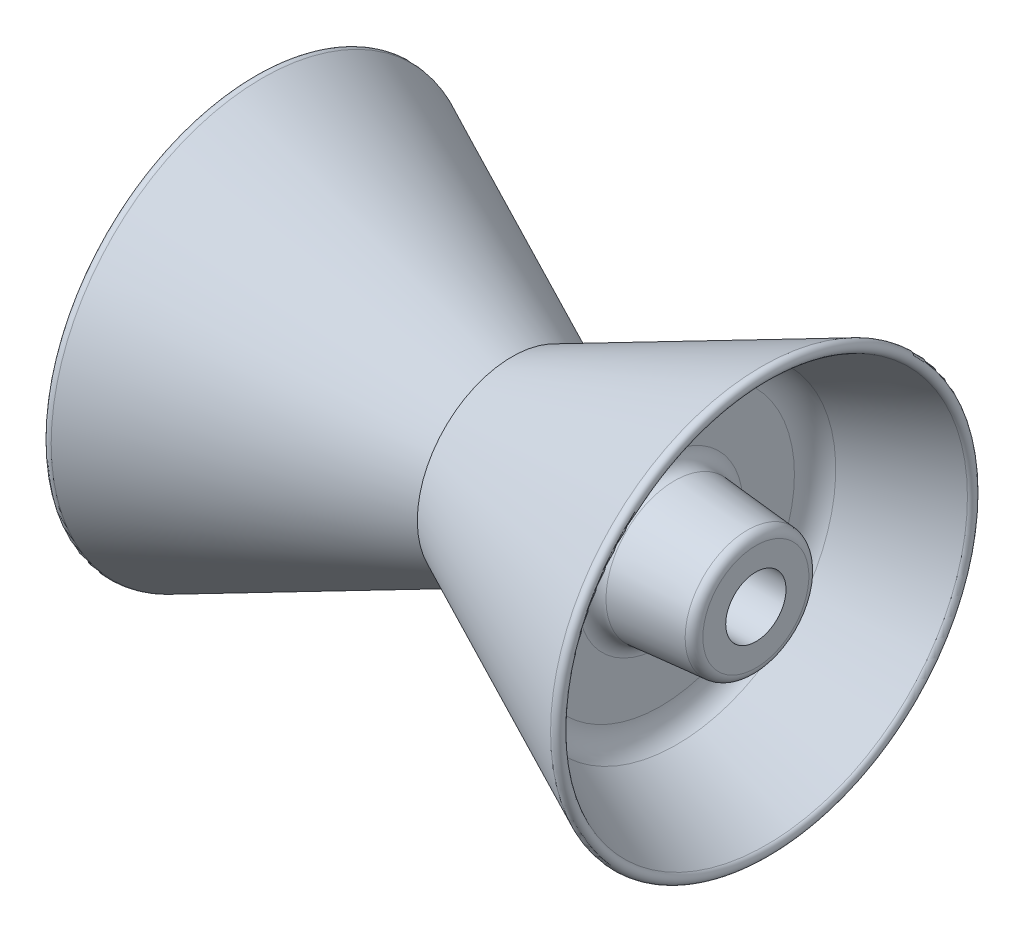
SolidWorks part; units mm, degrees
ref_plane "Front Plane" through (0, 0, 0) normal (0, 0, 1) x (1, 0, 0)
ref_plane "Top Plane" through (0, 0, 0) normal (0, 1, 0) x (1, 0, 0)
ref_plane "Right Plane" through (0, 0, 0) normal (1, 0, 0) x (0, 0, -1)
sketch "Sketch1" plane through (0, 0, 0) normal (0, 0, 1) x (1, 0, 0)
  line L0 (0, 0) -> (269.015, 125.4438)
  line L1 (0, 0) -> (-269.015, 125.4438)
  line L2 (0, -13.2405) -> (87.3215, 27.4781)
  line L3 (0, -13.2405) -> (-87.3215, 27.4781)
  line L4 (-160, 42.2566) -> (-160, -13.2405)
  line L5 (-130, 0.2889) -> (-130, -69.5162)
  line L6 (-160, 47.3795) -> (-160, -102.0162) construction
  line L7 (-336.887, -102.0162) -> (393.9288, -102.0162) construction
  line L8 (-262.7393, -69.5162) -> (-130, -69.5162)
  line L9 (-262.7393, -44.9222) -> (-262.7393, -69.5162)
  line L10 (-130, 47.3795) -> (-130, -102.0162) construction
  line L11 (0, -13.2405) -> (-274.0864, 114.5681) construction
  line L12 (-336.887, -69.5162) -> (393.9288, -69.5162) construction
  line L13 (-175, -28.2405) -> (-253.591, -34.9585)
  line L14 (-177.3215, 69.4458) -> (-274.0864, 114.5681)
  line L16 (130, 0.2889) -> (130, -69.5162)
  line L17 (262.7393, -44.9222) -> (262.7393, -69.5162)
  line L18 (175, -28.2405) -> (253.591, -34.9585)
  line L19 (160, 42.2566) -> (160, -13.2405)
  line L20 (130, -69.5162) -> (262.7393, -69.5162)
  line L21 (177.3215, 69.4458) -> (274.0864, 114.5681)
  line L23 (0, -13.2405) -> (274.0864, 114.5681) construction
  arc A0 (-269.015, 125.4438) -> (-274.0864, 114.5681) centre (-271.5507, 120.0059) ccw
  arc A1 (274.0864, 114.5681) -> (269.015, 125.4438) centre (271.5507, 120.0059) ccw
  arc A2 (-175, -28.2405) -> (-160, -13.2405) centre (-175, -13.2405) ccw
  arc A3 (-160, 42.2566) -> (-177.3215, 69.4458) centre (-190, 42.2566) ccw
  arc A4 (-87.3215, 27.4781) -> (-130, 0.2889) centre (-100, 0.2889) ccw
  arc A5 (87.3215, 27.4781) -> (130, 0.2889) centre (100, 0.2889) cw
  arc A6 (175, -28.2405) -> (160, -13.2405) centre (175, -13.2405) cw
  arc A7 (160, 42.2566) -> (177.3215, 69.4458) centre (190, 42.2566) cw
  arc A8 (-253.591, -34.9585) -> (-262.7393, -44.9222) centre (-252.7393, -44.9222) ccw
  arc A9 (262.7393, -44.9222) -> (253.591, -34.9585) centre (252.7393, -44.9222) ccw
  point P43 (-262.7393, -35.7405)
  point P46 (262.7393, -35.7405)
  dimension "D4" = 130
  dimension "D8" = 30
  dimension "D9" = 30
  dimension "D10" = 30
  dimension "D14" = 10
  dimension "D15" = 10
  dimension "D1" = 130
  dimension "D2" = 12
  dimension "D3" = 538.03
  dimension "D5" = 227.46
  dimension "D6" = 30
  dimension "D11" = 262.7393
  dimension "D12" = 262.7393
  dimension "D13" = 35.7405
  dimension "D7" = 32.5
revolve "Revolve1" add sketch "Sketch1" angle 360 about L7
